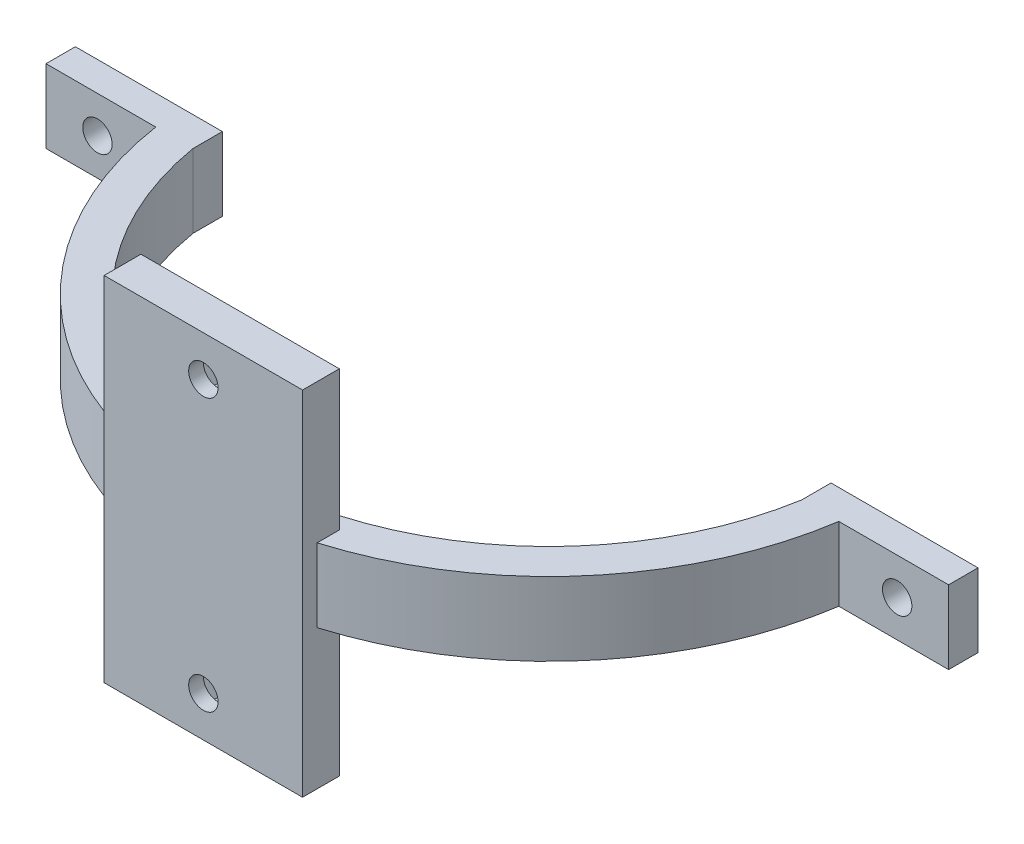
SolidWorks part; units mm, degrees
ref_plane "Спереди" through (0, 0, 0) normal (0, 0, 1) x (1, 0, 0)
ref_plane "Сверху" through (0, 0, 0) normal (0, 1, 0) x (1, 0, 0)
ref_plane "Справа" through (0, 0, 0) normal (1, 0, 0) x (0, 0, -1)
ref_plane "Плоскость4" through (0, 10, 0) normal (0, 1, 0) x (1, 0, 0)
sketch "Эскиз1" plane through (0, 10, 0) normal (0, 1, 0) x (1, 0, 0)
  line L0 (-13.5, -45.0194) -> (13.5, -45.0194)
  line L1 (46.4758, -7) -> (-46.4758, -7)
  arc A0 (13.5, -45.0194) -> (46.4758, -7) centre (0, 0) ccw
  arc A1 (-46.4758, -7) -> (-13.5, -45.0194) centre (0, 0) ccw
extrude "Бобышка-Вытянуть1" add sketch "Эскиз1" against normal blind 10
sketch "Эскиз2" plane through (0, 0, 45.0194) normal (0, 0, 1) x (1, 0, 0)
  line L0 (13.5, 0) -> (-13.5, 0)
  line L1 (-13.5, 0) -> (-13.5, 10)
  line L2 (-13.5, 10) -> (13.5, 10)
  line L3 (13.5, 10) -> (13.5, 0)
extrude "Бобышка-Вытянуть2" add sketch "Эскиз2" along normal blind 1.9806
sketch "Эскиз3" plane through (0, 0, 7) normal (0, 0, -1) x (-1, 0, 0)
  line L0 (61.4126, 0) -> (-61.4126, 0)
  line L1 (-61.4126, 0) -> (-61.4126, 10)
  line L2 (-61.4126, 10) -> (61.4126, 10)
  line L3 (61.4126, 10) -> (61.4126, 0)
extrude "Бобышка-Вытянуть3" add sketch "Эскиз3" along normal blind 4
sketch "Эскиз4" plane through (0, 0, 0) normal (0, -1, 0) x (1, 0, 0)
  line L0 (13.5, 42) -> (-13.5, 42)
  line L1 (-13.5, 42) -> (-13.5, 47)
  line L2 (-13.5, 47) -> (13.5, 47)
  line L3 (13.5, 47) -> (13.5, 42)
extrude "Бобышка-Вытянуть4" add sketch "Эскиз4" along normal blind 19
sketch "Эскиз5" plane through (0, 10, 0) normal (0, 1, 0) x (-1, 0, 0)
  line L0 (-41.4126, 3) -> (41.4126, 3)
  line L1 (41.4126, 3) -> (41.4126, 7)
  line L2 (-41.4126, 7) -> (-41.4126, 3)
  arc A0 (41.4126, 7) -> (-41.4126, 7) centre (0, 0) ccw
extrude "Вырез-Вытянуть1" cut sketch "Эскиз5" against normal through all
sketch "Эскиз6" plane through (0, 10, 0) normal (0, 1, 0) x (-1, 0, 0)
  line L0 (13.5, 42) -> (-13.5, 42)
  line L1 (-13.5, 42) -> (-13.5, 47)
  line L2 (-13.5, 47) -> (13.5, 47)
  line L3 (13.5, 47) -> (13.5, 42)
extrude "Бобышка-Вытянуть5" add sketch "Эскиз6" along normal blind 19
sketch "Эскиз7" plane through (0, 0, 42) normal (0, 0, -1) x (-1, 0, 0)
  line L0 (1.9919, 26.95) -> (-1.9919, 26.95)
  line L1 (-1.9919, 26.95) -> (-3.9837, 23.5)
  line L2 (-3.9837, 23.5) -> (-1.9919, 20.05)
  line L3 (-1.9919, 20.05) -> (1.9919, 20.05)
  line L4 (1.9919, 20.05) -> (3.9837, 23.5)
  line L5 (3.9837, 23.5) -> (1.9919, 26.95)
extrude "Вырез-Вытянуть2" cut sketch "Эскиз7" against normal blind 3
sketch "Эскиз8" plane through (0, 0, 42) normal (0, 0, -1) x (-1, 0, 0)
  line L0 (1.9919, -10.05) -> (-1.9919, -10.05)
  line L1 (-1.9919, -10.05) -> (-3.9837, -13.5)
  line L2 (-3.9837, -13.5) -> (-1.9919, -16.95)
  line L3 (-1.9919, -16.95) -> (1.9919, -16.95)
  line L4 (1.9919, -16.95) -> (3.9837, -13.5)
  line L5 (3.9837, -13.5) -> (1.9919, -10.05)
extrude "Вырез-Вытянуть3" cut sketch "Эскиз8" against normal blind 3
hole_wizard "Диаметр отверстия Ø4.0 (4)1" positions "Эскиз10" profile "Эскиз9" hole size "Ø4.0" standard "Ansi Metric"
sketch "Эскиз10" plane through (0, 0, 47) normal (0, 0, 1) x (1, 0, 0)
  point P0 (0, 23.5)
  point P1 (0, -13.5)
sketch "Эскиз9" plane through (0, 23.5, 47) normal (1, 0, 0) x (0, -1, 0)
  line L0 (0, 0) -> (0, 44)
  line L1 (0, 44) -> (2, 44)
  line L2 (2, 44) -> (2, 0)
  line L5 (2, 0) -> (0, 0)
  line L11 (0, -6.35) -> (0, 107.95) construction
  dimension "Диаметр сквозного отверстия" = 4
  dimension "Глубина сквозного отверстия" = 44
hole_wizard "Диаметр отверстия Ø4.0 (4)2" positions "Эскиз12" profile "Эскиз11" hole size "Ø4.0" standard "Ansi Metric"
sketch "Эскиз12" plane through (0, 0, 7) normal (0, 0, 1) x (1, 0, 0)
  point P0 (-54.4126, 5)
  point P1 (54.4126, 5)
sketch "Эскиз11" plane through (-54.4126, 5, 7) normal (1, 0, 0) x (0, -1, 0)
  line L0 (0, 0) -> (0, 4)
  line L1 (0, 4) -> (2, 4)
  line L2 (2, 4) -> (2, 0)
  line L5 (2, 0) -> (0, 0)
  line L11 (0, -6.35) -> (0, 107.95) construction
  dimension "Диаметр сквозного отверстия" = 4
  dimension "Глубина сквозного отверстия" = 4
